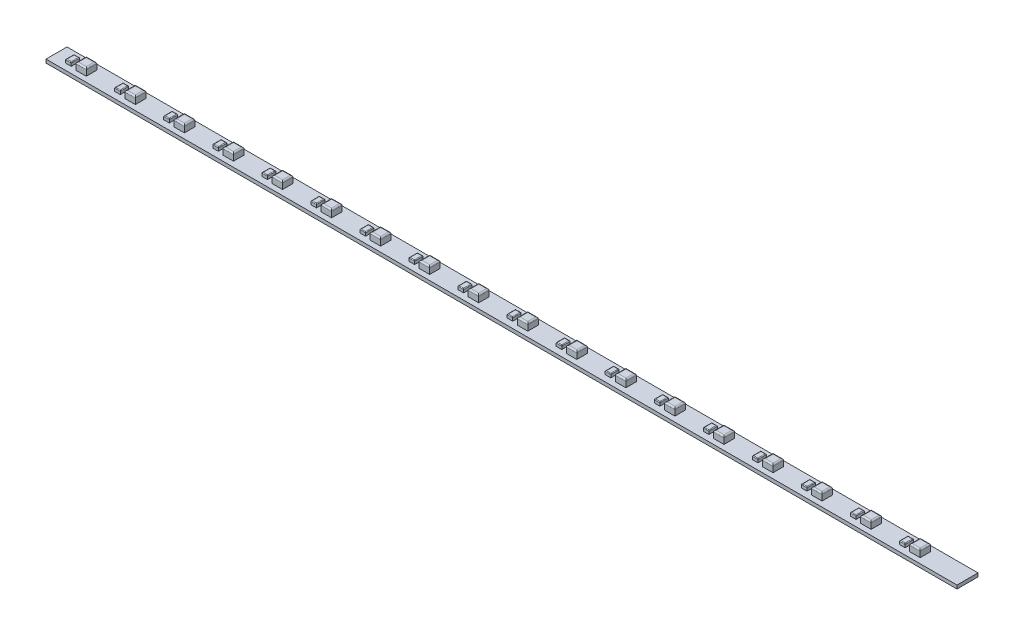
SolidWorks part; units mm, degrees
ref_plane "Front" through (0, 0, 0) normal (0, 0, 1) x (1, 0, 0)
ref_plane "Top" through (0, 0, 0) normal (0, 1, 0) x (1, 0, 0)
ref_plane "Right" through (0, 0, 0) normal (1, 0, 0) x (0, 0, -1)
sketch "草图1" plane through (0, 0, 0) normal (0, 1, 0) x (1, 0, 0)
  line L0 (-65, 1.5) -> (65, -1.5) construction
  line L1 (-65, -1.5) -> (65, -1.5)
  line L2 (-65, -1.5) -> (-65, 1.5)
  line L3 (-65, 1.5) -> (65, 1.5)
  line L4 (65, -1.5) -> (65, 1.5)
  line L5 (-65, -1.5) -> (65, 1.5) construction
  dimension "D1" = 3
  dimension "D2" = 130
extrude "凸台-拉伸1" add sketch "草图1" along normal blind 0.5
sketch "草图2" plane through (0, 0.5, 0) normal (0, 1, 0) x (1, 0, 0)
  line L0 (-65, -1.5) -> (65, -1.5) construction
  line L1 (-61.5, 0.75) -> (-60, 0.75)
  line L2 (-61.5, 0.75) -> (-61.5, -0.75)
  line L3 (-61.5, -0.75) -> (-60, -0.75)
  line L4 (-60, 0.75) -> (-60, -0.75)
  line L5 (-65, 1.5) -> (-65, -1.5) construction
  dimension "D1" = 1.5
  dimension "D2" = 1.5
  dimension "D3" = 0.75
  dimension "D4" = 3.5
extrude "凸台-拉伸2" add sketch "草图2" along normal blind 1
sketch "草图3" plane through (0, 0.5, 0) normal (0, 1, 0) x (1, 0, 0)
  line L0 (-61.5, -0.75) -> (-60, -0.75) construction
  line L1 (-63.1, 0.6) -> (-62.3, 0.6)
  line L2 (-63.1, 0.6) -> (-63.1, -0.6)
  line L3 (-63.1, -0.6) -> (-62.3, -0.6)
  line L4 (-62.3, 0.6) -> (-62.3, -0.6)
  line L5 (-61.5, 0.75) -> (-61.5, -0.75) construction
  dimension "D1" = 1.2
  dimension "D2" = 0.8
  dimension "D3" = 0.15
  dimension "D4" = 0.8
extrude "凸台-拉伸3" add sketch "草图3" along normal blind 0.5
fillet "圆角1" radius 0.2 4 edges at (-60.75, 1.5, -0.75) (-60, 1.5, 0) (-60.75, 1.5, 0.75) (-61.5, 1.5, 0)
fillet "圆角2" radius 0.1 4 edges at (-62.7, 1, -0.6) (-62.3, 1, 0) (-62.7, 1, 0.6) (-63.1, 1, 0)
pattern_linear "阵列(线性)3" count 18 spacing 7 along (1, 0, 0) of "凸台-拉伸2", "凸台-拉伸3", "圆角1", "圆角2"
